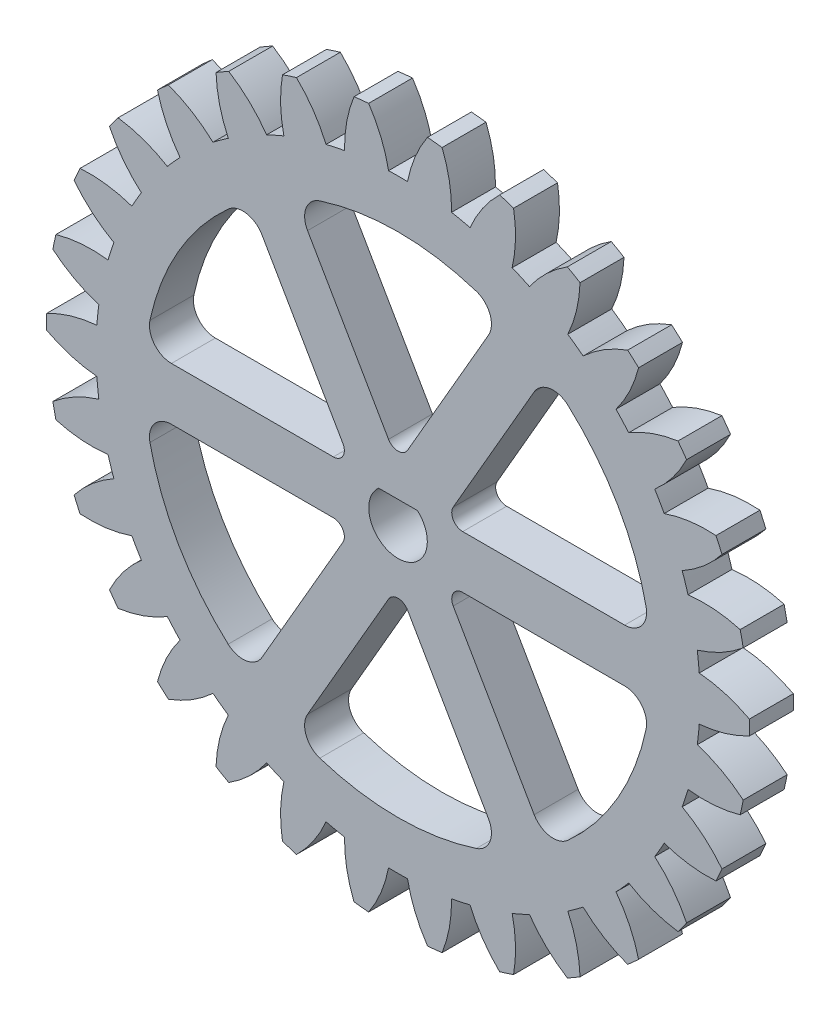
SolidWorks part; units mm, degrees
ref_plane "Front Plane" through (0, 0, 0) normal (0, 0, 1) x (1, 0, 0)
ref_plane "Top Plane" through (0, 0, 0) normal (0, 1, 0) x (1, 0, 0)
ref_plane "Right Plane" through (0, 0, 0) normal (1, 0, 0) x (0, 0, -1)
sketch "Sketch1" plane through (0, 0, 0) normal (0, 0, 1) x (1, 0, 0)
  circle A0 centre (0, 0) radius 24
  dimension "addendumDiameter " = 48
extrude "Boss-Extrude1" add sketch "Sketch1" along normal blind 3
sketch "Sketch2" plane through (0, 0, 3) normal (0, 0, 1) x (1, 0, 0)
  line L0 (0, 0) -> (0, 31.2008) construction
  line L1 (0, 0) -> (-2.5588, 24.3457) construction
  line L2 (-1.1628, 22.3336) -> (-2.3344, 22.2104) construction
  circle A0 centre (0, 0) radius 20.625 construction
  circle A1 centre (0, 0) radius 21.1431 construction
  circle A2 centre (0, 0) radius 22.5 construction
  arc A3 (-2.0098, 23.9157) -> (-0.6465, 20.6149) centre (-9.4812, 18.898) cw
  arc A4 (-2.0098, 23.9157) -> (2.0098, 23.9157) centre (0, 0) cw
  arc A5 (-0.6465, 20.6149) -> (0.6465, 20.6149) centre (0, 0) cw
  circle A6 centre (0, 0) radius 24 construction
  arc A7 (2.0098, 23.9157) -> (0.6465, 20.6149) centre (9.4812, 18.898) ccw
  dimension "dedendumCircle" = 41.25
  dimension "baseDiameter" = 42.2862
  dimension "pitchDiameter" = 45
  dimension "D2" = 9
  dimension "D1" = 6
  dimension "D3" = 1.1781
extrude "Cut-Extrude1" cut sketch "Sketch2" against normal through all
pattern_circular "CirPattern1" count 30 over 360 about axis through (0, 0, 0) along (0, 0, 1) of "Cut-Extrude1"
sketch "Sketch3" plane through (0, 0, 3) normal (0, 0, 1) x (1, 0, 0)
  line L0 (0, 0) -> (-35.4164, 0) construction
  line L1 (0, 0) -> (-16.4465, 28.4861) construction
  line L5 (-4.4167, 1.8) -> (-15.4771, 1.8)
  line L6 (-3.7672, 2.925) -> (-9.2974, 12.5036)
  arc A1 (-16.9441, 3.6128) -> (-11.6008, 12.8676) centre (0, 0) cw
  arc A2 (-9.2974, 12.5036) -> (-11.6008, 12.8676) centre (-10.5964, 11.7536) ccw
  circle A3 centre (0, 0) radius 17.325 construction
  arc A4 (-15.4771, 1.8) -> (-16.9441, 3.6128) centre (-15.4771, 3.3) cw
  arc A5 (-4.4167, 1.8) -> (-3.7672, 2.925) centre (-4.4167, 2.55) ccw
  point P10 (-10.1745, 14.0227)
  point P14 (-17.2312, 1.8)
  dimension "D5" = 34.65
  dimension "D3" = 1.5
  dimension "D4" = 0.75
  dimension "D1" = 60
  dimension "D2" = 1.8
extrude "Cut-Extrude3" cut sketch "Sketch3" against normal through all
pattern_circular "CirPattern2" count 6 over 360 about axis through (0, 0, 0) along (0, 0, 1) of "Cut-Extrude3"
sketch "Sketch4" plane through (0, 0, 3) normal (0, 0, 1) x (1, 0, 0)
  line L0 (-1.3229, 1.5) -> (1.3229, 1.5)
  line L1 (1.65, 0) -> (-1.65, 0) construction
  arc A0 (-1.3229, 1.5) -> (1.3229, 1.5) centre (0, 0) ccw
  dimension "D1" = 2
  dimension "D2" = 1.5
extrude "Cut-Extrude4" cut sketch "Sketch4" against normal through all
equation "\"module\"= 1.5"
equation "\"teeth\"= 30"
equation "\"pressureAngle\"= 20deg"
equation "\"gearThickness\"= 3"
equation "\"addendumFactor\"= 1"
equation "\"dedendumFactor\"= 1.25"
equation "\"pitch\"= 1/\"module\""
equation "\"pitchDiameter\"= \"teeth\" / \"pitch\""
equation "\"addendum\"= \"addendumFactor\" / \"pitch\""
equation "\"dedendum\"= \"dedendumFactor\" / \"pitch\""
equation "\"addendumDiameter @Sketch1\"= \"pitchDiameter\" + 2 * \"addendum\""
equation "\"D1@Boss-Extrude1\"= \"gearThickness\""
equation "\"dedendumCircle@Sketch2\" = \"pitchDiameter\" - 2 * \"dedendum\""
equation "\"baseDiameter@Sketch2\"=\"pitchDiameter\" * cos ( \"pressureAngle\" )"
equation "\"pitchDiameter@Sketch2\"=\"pitchDiameter\""
equation "\"D1@Sketch2\"=180/\"teeth\""
equation "\"D2@Sketch2\"=\"pitchDiameter\"/5"
equation "\"D3@Sketch2\"=PI / 2 / \"pitch\" / 2"
equation "\"D1@CirPattern1\"=\"teeth\""
equation "\"D5@Sketch3\"=\"pitchDiameter\"*.77"
equation "\"D2@Sketch3\"=\"module\"*\"teeth\"*.04"
